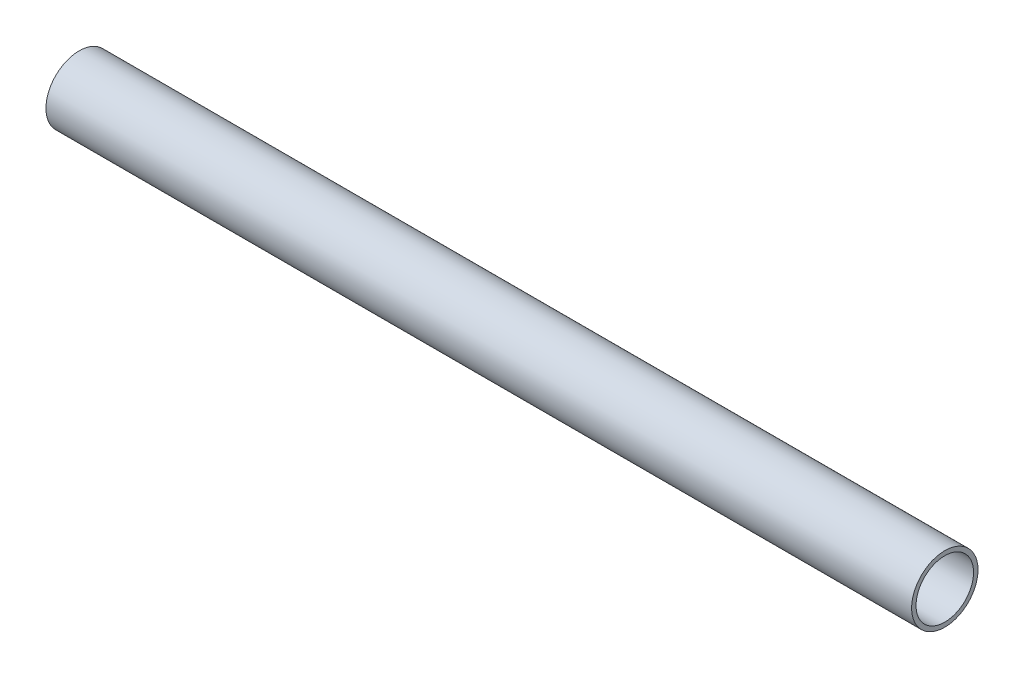
SolidWorks part; units mm, degrees
ref_plane "前视基准面" through (0, 0, 0) normal (0, 0, 1) x (1, 0, 0)
ref_plane "上视基准面" through (0, 0, 0) normal (0, 1, 0) x (1, 0, 0)
ref_plane "右视基准面" through (0, 0, 0) normal (1, 0, 0) x (0, 0, -1)
sketch "草图1" plane through (0, 0, 0) normal (1, 0, 0) x (0, 0, -1)
  circle A0 centre (0, 0) radius 7.5
  circle A1 centre (0, 0) radius 6.5
  dimension "D1" = 13
  dimension "D2" = 15
extrude "凸台-拉伸1" add sketch "草图1" along normal blind 195.58
